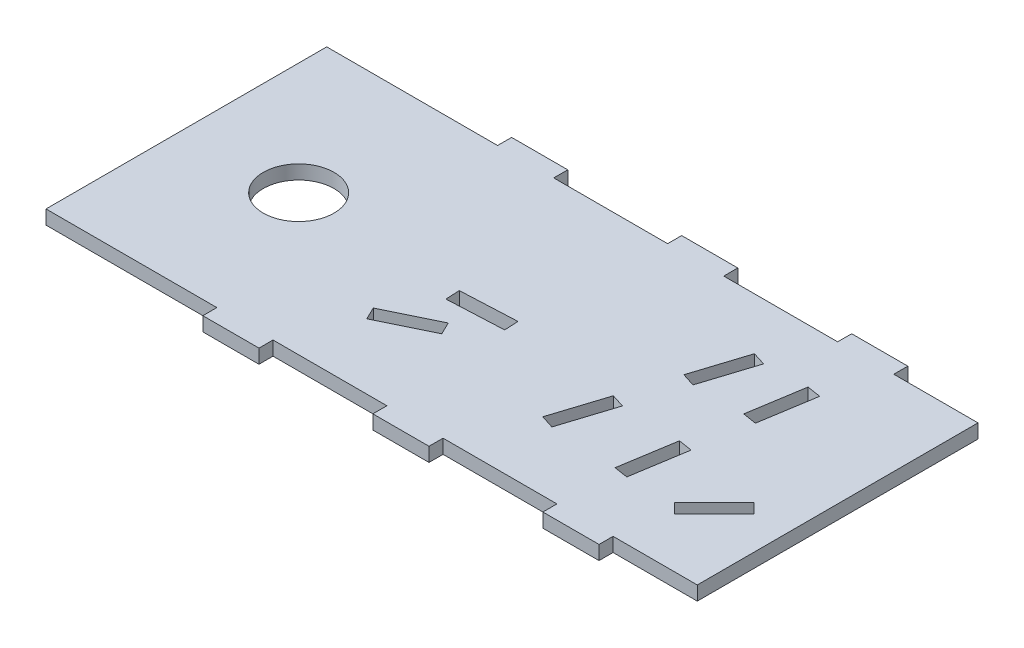
SolidWorks part; units mm, degrees
ref_plane "Front Plane" through (0, 0, 0) normal (0, 0, 1) x (1, 0, 0)
ref_plane "Top Plane" through (0, 0, 0) normal (0, 1, 0) x (1, 0, 0)
ref_plane "Right Plane" through (0, 0, 0) normal (1, 0, 0) x (0, 0, -1)
sketch "Sketch1" plane through (0, 0, 0) normal (0, 1, 0) x (1, 0, 0)
  line L0 (128.27, 0) -> (128.27, -3.175)
  line L1 (0, 0) -> (38.6483, 0)
  line L2 (0, 0) -> (0, 63.5)
  line L3 (0, 63.5) -> (38.6483, 63.5)
  line L4 (147.32, 0) -> (147.32, 63.5)
  line L5 (128.27, -3.175) -> (115.57, -3.175)
  line L6 (115.57, -3.175) -> (115.57, 0)
  line L7 (0, 31.75) -> (147.32, 31.75) construction
  line L8 (128.27, 0) -> (147.32, 0)
  line L9 (89.8091, 0) -> (89.8091, -3.175)
  line L10 (89.8091, -3.175) -> (77.1091, -3.175)
  line L11 (77.1091, -3.175) -> (77.1091, 0)
  line L12 (51.3483, 0) -> (51.3483, -3.175)
  line L13 (51.3483, -3.175) -> (38.6483, -3.175)
  line L14 (38.6483, -3.175) -> (38.6483, 0)
  line L15 (51.3483, 0) -> (77.1091, 0)
  line L16 (89.8091, 0) -> (115.57, 0)
  line L17 (38.6483, 66.675) -> (38.6483, 63.5)
  line L18 (51.3483, 66.675) -> (38.6483, 66.675)
  line L19 (51.3483, 63.5) -> (51.3483, 66.675)
  line L20 (77.1091, 66.675) -> (77.1091, 63.5)
  line L21 (89.8091, 66.675) -> (77.1091, 66.675)
  line L22 (128.27, 63.5) -> (128.27, 66.675)
  line L23 (128.27, 66.675) -> (115.57, 66.675)
  line L24 (115.57, 66.675) -> (115.57, 63.5)
  line L25 (89.8091, 63.5) -> (89.8091, 66.675)
  line L26 (51.3483, 63.5) -> (77.1091, 63.5)
  line L27 (89.8091, 63.5) -> (115.57, 63.5)
  line L28 (128.27, 63.5) -> (147.32, 63.5)
  line L29 (124.2129, 0) -> (124.2129, 63.5) construction
  line L30 (124.2129, 50.8) -> (118.1936, 13.1785) construction
  line L31 (124.2129, 50.8) -> (122.2064, 38.2595)
  line L32 (122.2064, 38.2595) -> (119.0713, 38.7611)
  line L33 (119.0713, 38.7611) -> (121.0777, 51.3016)
  line L34 (121.0777, 51.3016) -> (124.2129, 50.8)
  line L35 (121.2032, 31.9892) -> (129.8126, 30.6118) construction
  line L36 (117.0649, 26.2206) -> (115.0585, 13.6801)
  line L37 (120.2, 25.719) -> (117.0649, 26.2206)
  line L38 (118.1936, 13.1785) -> (120.2, 25.719)
  line L39 (115.0585, 13.6801) -> (118.1936, 13.1785)
  line L40 (111.5129, 67.0991) -> (111.5129, 3.5991) construction
  line L41 (111.5129, 50.8) -> (99.9292, 14.5036) construction
  line L42 (124.2129, 50.8) -> (0, 50.8) construction
  line L43 (111.5129, 50.8) -> (107.6516, 38.7012)
  line L44 (107.6516, 38.7012) -> (104.6269, 39.6665)
  line L45 (104.6269, 39.6665) -> (108.4882, 51.7653)
  line L46 (108.4882, 51.7653) -> (111.5129, 50.8)
  line L47 (105.721, 32.6518) -> (108.4655, 31.7759) construction
  line L48 (100.7657, 27.5677) -> (96.9045, 15.4689)
  line L49 (103.7904, 26.6024) -> (100.7657, 27.5677)
  line L50 (99.9292, 14.5036) -> (103.7904, 26.6024)
  line L51 (96.9045, 15.4689) -> (99.9292, 14.5036)
  line L52 (139.8405, 63.5) -> (139.8405, 0) construction
  line L53 (139.8405, 20.3013) -> (130.8602, 11.321) construction
  line L54 (139.8405, 20.3013) -> (130.8602, 11.321)
  line L55 (130.8602, 11.321) -> (128.6151, 13.5661)
  line L56 (128.6151, 13.5661) -> (137.5954, 22.5463)
  line L57 (137.5954, 22.5463) -> (139.8405, 20.3013)
  line L58 (69.2266, 63.5) -> (69.2266, 0) construction
  line L59 (139.8405, 20.3013) -> (0, 20.3013) construction
  line L60 (69.2266, 20.3013) -> (57.8022, 14.7539)
  line L61 (57.8022, 14.7539) -> (56.4153, 17.61)
  line L62 (56.4153, 17.61) -> (67.8397, 23.1574)
  line L63 (67.8397, 23.1574) -> (69.2266, 20.3013)
  line L64 (75.5766, 63.5) -> (75.5766, 0) construction
  line L65 (75.5766, 28.1721) -> (62.8907, 27.5739)
  line L66 (62.8907, 27.5739) -> (62.7411, 30.7453)
  line L67 (62.7411, 30.7453) -> (75.427, 31.3436)
  line L68 (75.427, 31.3436) -> (75.5766, 28.1721)
  circle A0 centre (25.4, 31.75) radius 8
  point P36 (120.0745, 45.0314)
  point P66 (69.2266, 20.3013)
  dimension "D27" = 25.4
  dimension "D28" = 16
  dimension "D1" = 63.5
  dimension "D2" = 147.32
  dimension "D3" = 19.05
  dimension "D4" = 12.7
  dimension "D6" = 3.175
  dimension "D7" = 38.1
  dimension "D8" = 9.09
  dimension "D9" = 3.175
  dimension "D10" = 12.7
  dimension "D11" = 38.1
  dimension "D12" = 17.7
  dimension "D13" = 12.7
  dimension "D14" = 12.7
  dimension "D15" = 3.175
  dimension "D16" = 12.7
  dimension "D17" = 45
  dimension "D18" = 12.7
  dimension "D19" = 3.175
  dimension "D20" = 64.1
  dimension "D21" = 12.7
  dimension "D22" = 3.175
  dimension "D23" = 12.7
  dimension "D24" = 87.3
  dimension "D25" = 3.175
  dimension "D26" = 6.35
  dimension "D5" = 3
extrude "Boss-Extrude1" add sketch "Sketch1" along normal blind 3.175
